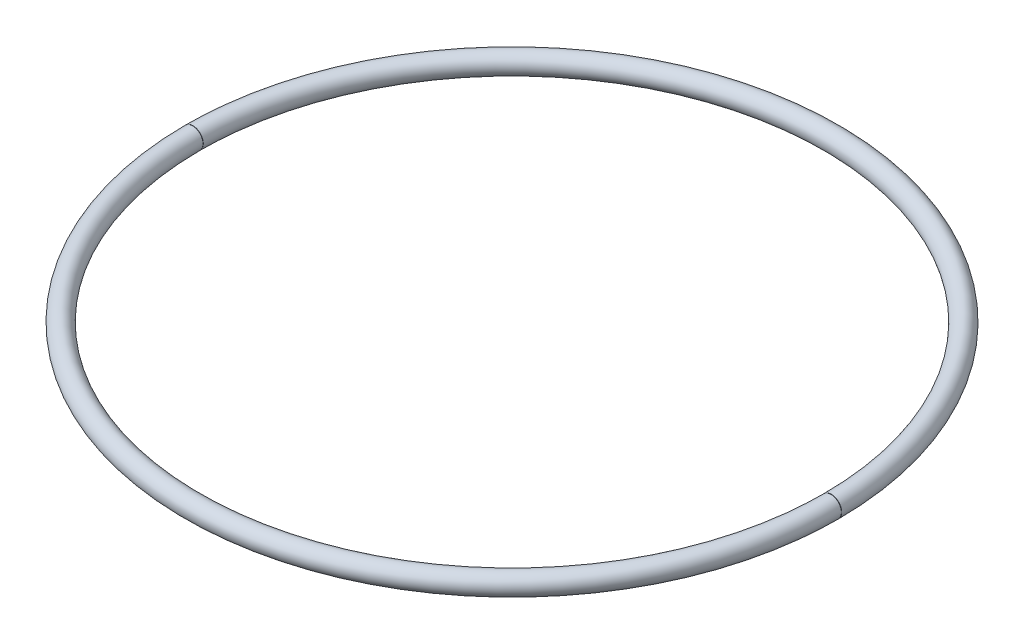
SolidWorks part; units mm, degrees
material "6061 Alloy"
ref_plane "Front Plane" through (0, 0, 0) normal (0, 0, 1) x (1, 0, 0)
ref_plane "Top Plane" through (0, 0, 0) normal (0, 1, 0) x (1, 0, 0)
ref_plane "Right Plane" through (0, 0, 0) normal (1, 0, 0) x (0, 0, -1)
sketch "Sketch1" plane through (0, 0, 0) normal (0, 1, 0) x (1, 0, 0)
  line L1 (758.825, -0.3969) -> (809.625, -0.3969)
  line L2 (758.825, -0.3969) -> (758.825, 0.3969)
  line L3 (758.825, 0.3969) -> (809.625, 0.3969)
  line L4 (809.625, -0.3969) -> (809.625, 0.3969)
  line L5 (758.825, -0.3969) -> (809.625, 0.3969) construction
  line L6 (758.825, 0.3969) -> (809.625, -0.3969) construction
  circle A0 centre (0, 0) radius 784.225
  point P3 (784.225, 0)
  point P8 (809.625, 0)
  dimension "D1" = 1568.45
  dimension "D2" = 50.8
  dimension "D3" = 0.7937
  dimension "D4" = 809.625
sketch "Sketch24" plane through (0, 0, 0) normal (0, 1, 0) x (1, 0, 0)
  line L2 (758.825, 0.3969) -> (809.625, 0.3969) construction
  line L3 (758.825, -0.3969) -> (809.625, -0.3969) construction
  circle A0 centre (0, 0) radius 784.225 construction
  arc A1 (784.2249, 0.3969) -> (784.2249, -0.3969) centre (0, 0) ccw
sweep "Sweep2" add path "Sketch24" circular profile diameter 50.8 parameters "D3"=50.8
shell "Shell1" thickness 3.175
sketch "Sketch25" plane through (0, 0, 0) normal (0, 1, 0) x (1, 0, 0)
  line L0 (758.8249, 0.384) -> (809.6249, 0.4097) construction
  line L1 (-825.5, 0.3663) -> (-723.9, 0.3663)
  line L2 (-825.5, 0.3663) -> (-825.5, -0.3663)
  line L3 (-825.5, -0.3663) -> (-723.9, -0.3663)
  line L4 (-723.9, 0.3663) -> (-723.9, -0.3663)
  line L5 (-774.7, -0.3663) -> (-774.7, 0.3663) construction
  line L6 (-825.5, 0) -> (-723.9, 0) construction
  point P0 (-774.7, 0)
  point P4 (0, 0)
  dimension "D1" = 101.6
  dimension "30" = 723.9
extrude "Cut-Extrude1" cut sketch "Sketch25" against normal through all both and the other way through all
